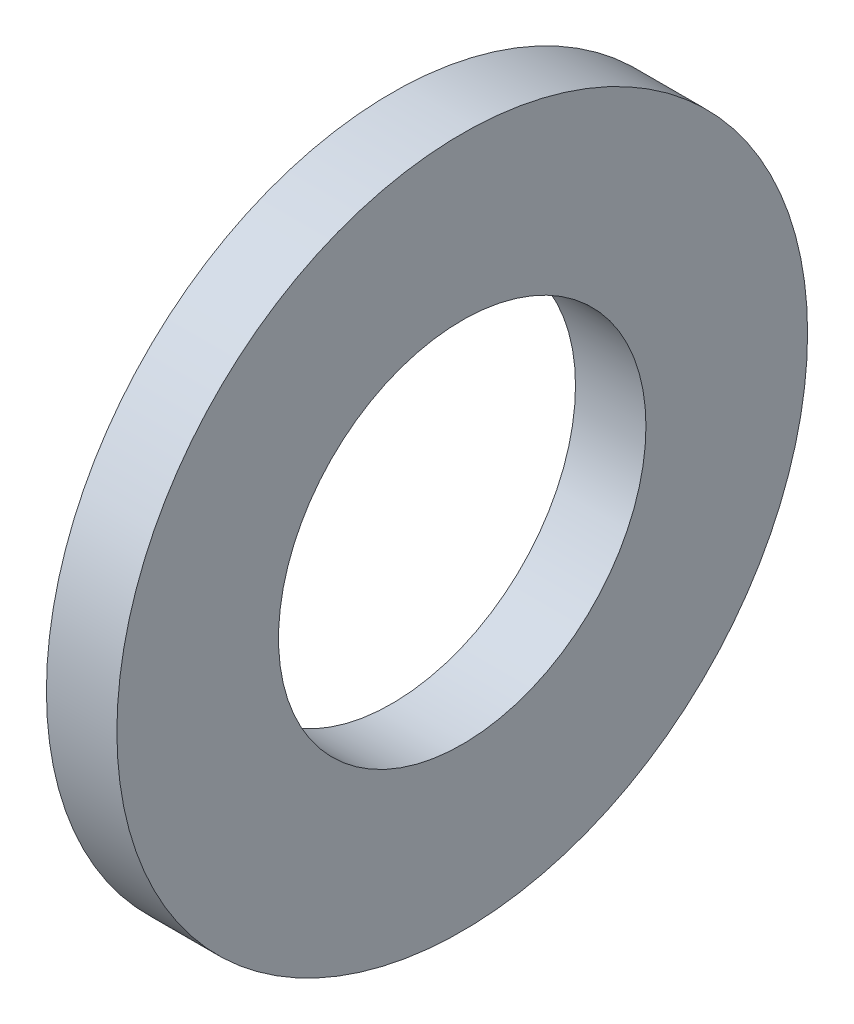
SolidWorks part; units mm, degrees
ref_plane "Front Plane" through (0, 0, 0) normal (0, 0, 1) x (1, 0, 0)
ref_plane "Top Plane" through (0, 0, 0) normal (0, 1, 0) x (1, 0, 0)
ref_plane "Right Plane" through (0, 0, 0) normal (1, 0, 0) x (0, 0, -1)
sketch "Sketch1" plane through (0, 0, 0) normal (1, 0, 0) x (0, 0, -1)
  circle A0 centre (0, 0) radius 6.35
  circle A1 centre (0, 0) radius 3.3782
  dimension "OD" = 12.7
  dimension "ID" = 6.7564
extrude "Boss-Extrude1" add sketch "Sketch1" along normal blind 1.2954
